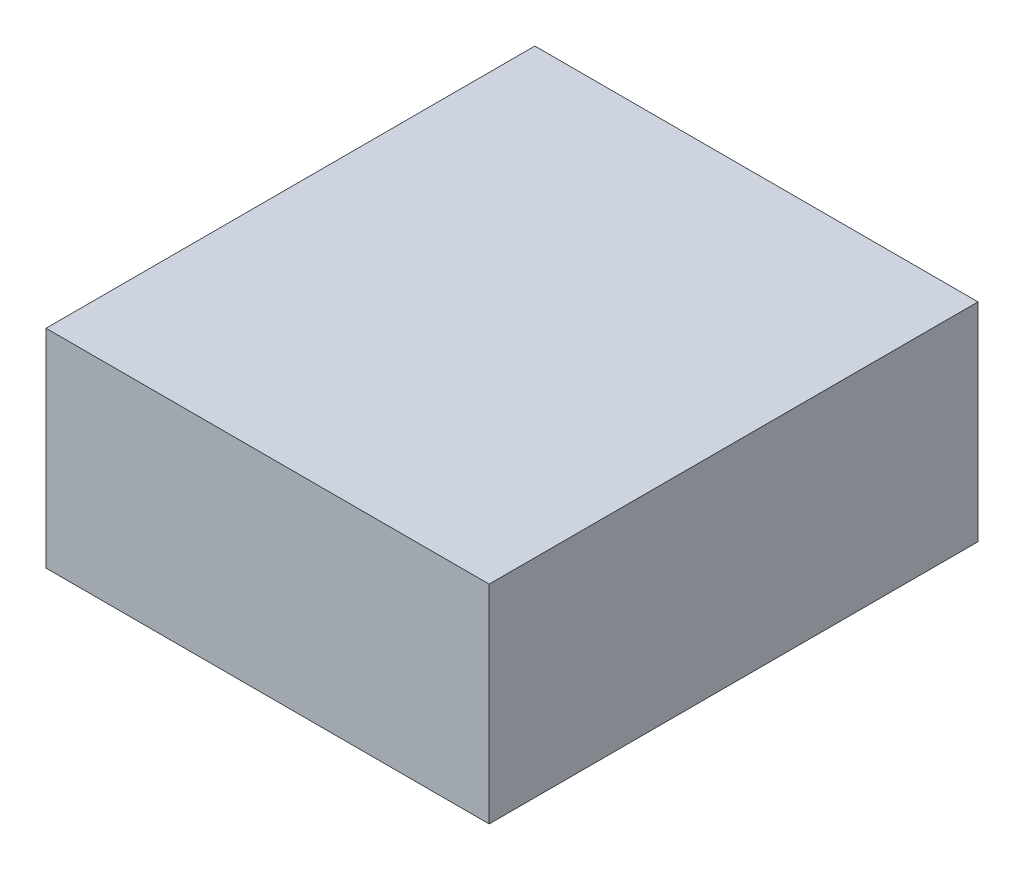
SolidWorks part; units mm, degrees
ref_plane "Front Plane" through (0, 0, 0) normal (0, 0, 1) x (1, 0, 0)
ref_plane "Top Plane" through (0, 0, 0) normal (0, 1, 0) x (1, 0, 0)
ref_plane "Right Plane" through (0, 0, 0) normal (1, 0, 0) x (0, 0, -1)
sketch "Sketch1" plane through (0, 0, 0) normal (0, 1, 0) x (1, 0, 0)
  line L1 (-32, 35.3) -> (32, 35.3)
  line L2 (-32, 35.3) -> (-32, -35.3)
  line L3 (-32, -35.3) -> (32, -35.3)
  line L4 (32, 35.3) -> (32, -35.3)
  line L5 (-32, 35.3) -> (32, -35.3) construction
  line L6 (-32, -35.3) -> (32, 35.3) construction
  point P0 (0, 0)
  dimension "D1" = 70.6
  dimension "D2" = 64
extrude "Boss-Extrude1" add sketch "Sketch1" along normal blind 30
